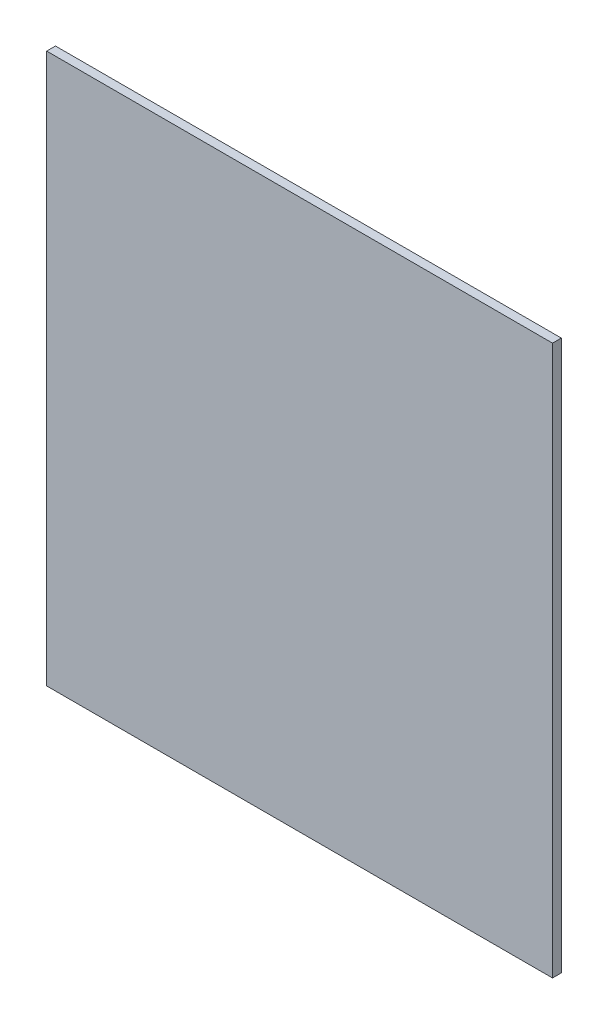
SolidWorks part; units mm, degrees
material "ABS PC"
ref_plane "Front Plane" through (0, 0, 0) normal (0, 0, 1) x (1, 0, 0)
ref_plane "Top Plane" through (0, 0, 0) normal (0, 1, 0) x (1, 0, 0)
ref_plane "Right Plane" through (0, 0, 0) normal (1, 0, 0) x (0, 0, -1)
sketch "Sketch1" plane through (0, 0, 0) normal (0, 0, 1) x (1, 0, 0)
  line L1 (-115, -125) -> (115, -125)
  line L2 (-115, -125) -> (-115, 125)
  line L3 (-115, 125) -> (115, 125)
  line L4 (115, -125) -> (115, 125)
  line L5 (-115, -125) -> (115, 125) construction
  line L6 (-115, 125) -> (115, -125) construction
  point P0 (0, 0)
  dimension "D1" = 230
  dimension "D2" = 250
extrude "Boss-Extrude1" add sketch "Sketch1" along normal blind 4
